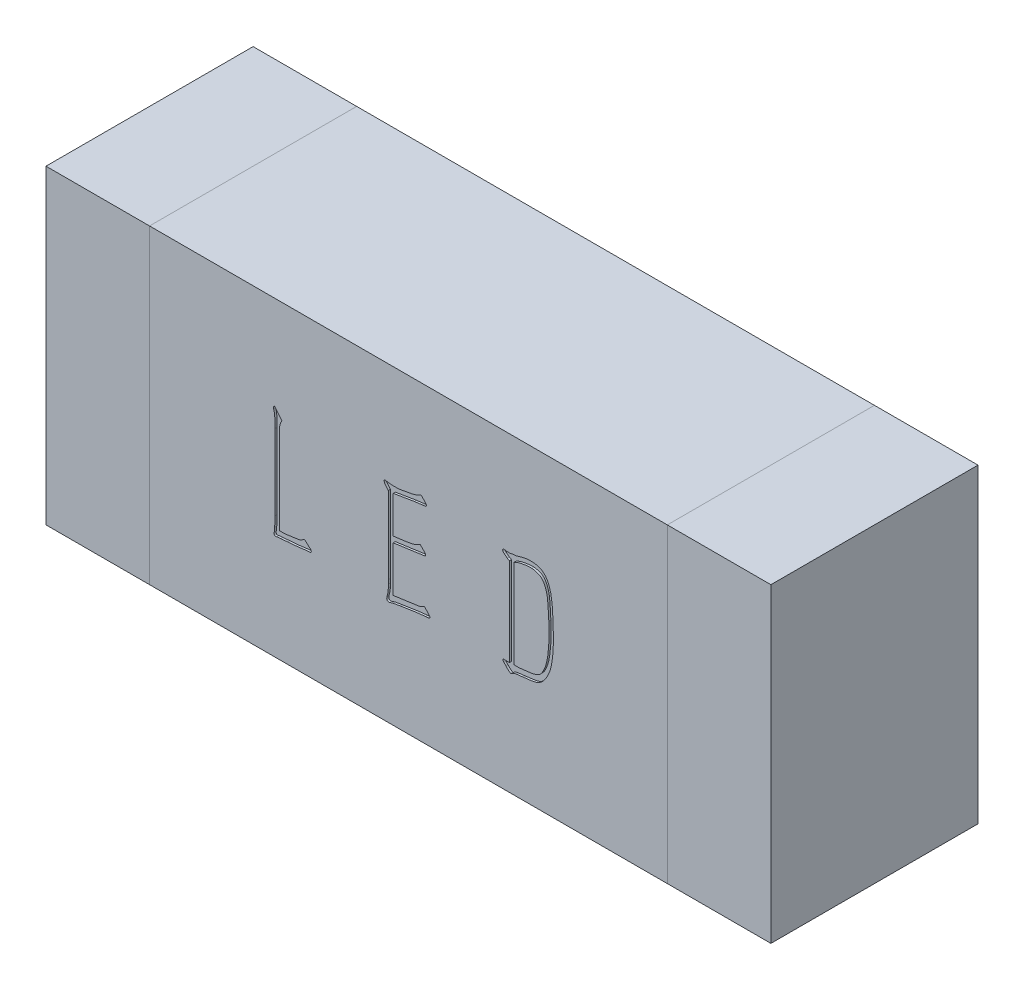
SolidWorks part; units mm, degrees
ref_plane "前视基准面" through (0, 0, 0) normal (0, 0, 1) x (1, 0, 0)
ref_plane "上视基准面" through (0, 0, 0) normal (0, 1, 0) x (1, 0, 0)
ref_plane "右视基准面" through (0, 0, 0) normal (1, 0, 0) x (0, 0, -1)
sketch "草图1" plane through (0, 0, 0) normal (0, 0, 1) x (1, 0, 0)
  line L1 (-1.25, 0.75) -> (1.25, 0.75)
  line L2 (-1.25, 0.75) -> (-1.25, -0.75)
  line L3 (-1.25, -0.75) -> (1.25, -0.75)
  line L4 (1.25, 0.75) -> (1.25, -0.75)
  line L5 (-1.25, 0.75) -> (1.25, -0.75) construction
  line L6 (-1.25, -0.75) -> (1.25, 0.75) construction
  point P0 (0, 0)
extrude "凸台-拉伸1" add sketch "草图1" along normal blind 1
sketch "草图2" plane through (0, 0, 0) normal (0, 0, -1) x (-1, 0, 0)
  line L0 (1.25, -0.75) -> (-1.25, -0.75) construction
  line L1 (1.25, 0.75) -> (1.75, 0.75)
  line L2 (1.25, 0.75) -> (1.25, -0.75)
  line L3 (1.25, -0.75) -> (1.75, -0.75)
  line L4 (1.75, 0.75) -> (1.75, -0.75)
  line L5 (-1.25, 0.75) -> (-1.75, 0.75)
  line L6 (-1.25, 0.75) -> (-1.25, -0.75)
  line L7 (-1.25, -0.75) -> (-1.75, -0.75)
  line L8 (-1.75, 0.75) -> (-1.75, -0.75)
  dimension "D1" = 0.5
  dimension "D2" = 0.5
extrude "凸台-拉伸2" add sketch "草图2" against normal blind 1 separate body
sketch "草图4" plane through (0, 0, 1) normal (0, 0, 1) x (1, 0, 0)
  line L0 (-0.68, -0.2928) -> (0.6895, -0.2928) construction
  text T0 "L E D" font "汉仪长仿宋体" height in points 2
extrude "切除-拉伸1" cut sketch "草图4" against normal blind 0.01
